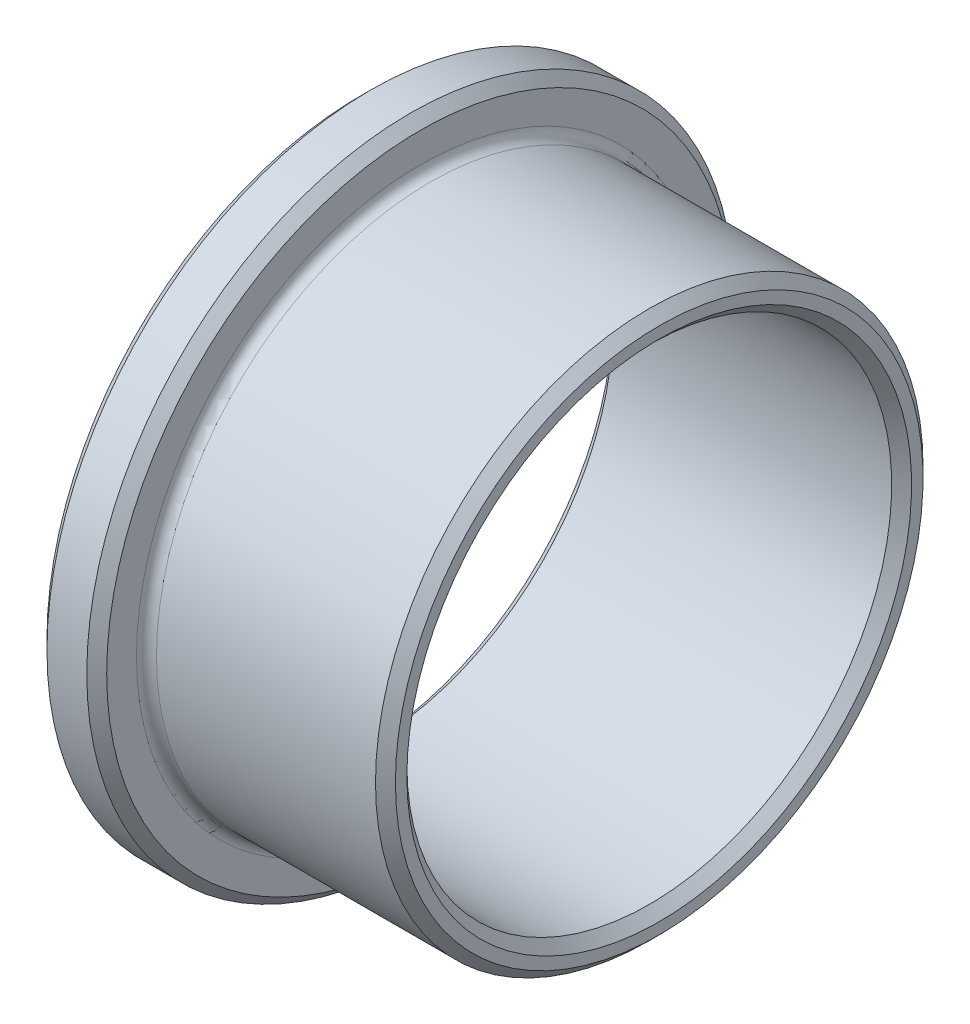
SolidWorks part; units mm, degrees
material "Phosphor bronze 10% D, UNS C52400"
ref_plane "Front Plane" through (0, 0, 0) normal (0, 0, 1) x (1, 0, 0)
ref_plane "Top Plane" through (0, 0, 0) normal (0, 1, 0) x (1, 0, 0)
ref_plane "Right Plane" through (0, 0, 0) normal (1, 0, 0) x (0, 0, -1)
sketch "Sketch1" plane through (0, 0, 0) normal (0, 0, 1) x (1, 0, 0)
  line L0 (0, 24.35) -> (30, 24.35)
  line L1 (30, 24.35) -> (30, 27.5)
  line L2 (30, 27.5) -> (6, 27.5)
  line L3 (6, 27.5) -> (6, 32.5)
  line L4 (6, 32.5) -> (0, 32.5)
  line L5 (0, 32.5) -> (0, 24.35)
  line L6 (0, 0) -> (44.8454, 0) construction
  dimension "D1" = 48.7
  dimension "D2" = 6
  dimension "D3" = 65
  dimension "D4" = 30
  dimension "D5" = 55
revolve "Revolve1" add sketch "Sketch1" angle 360 about L6
chamfer "Chamfer1" distance 1 angle 45 5 edges at (0, 0, 24.35) (30, 0, 24.35) (6, 0, 32.5) (0, 0, 32.5) (30, 0, 27.5)
fillet "Fillet1" radius 1 1 edges at (6, 0, 27.5)
